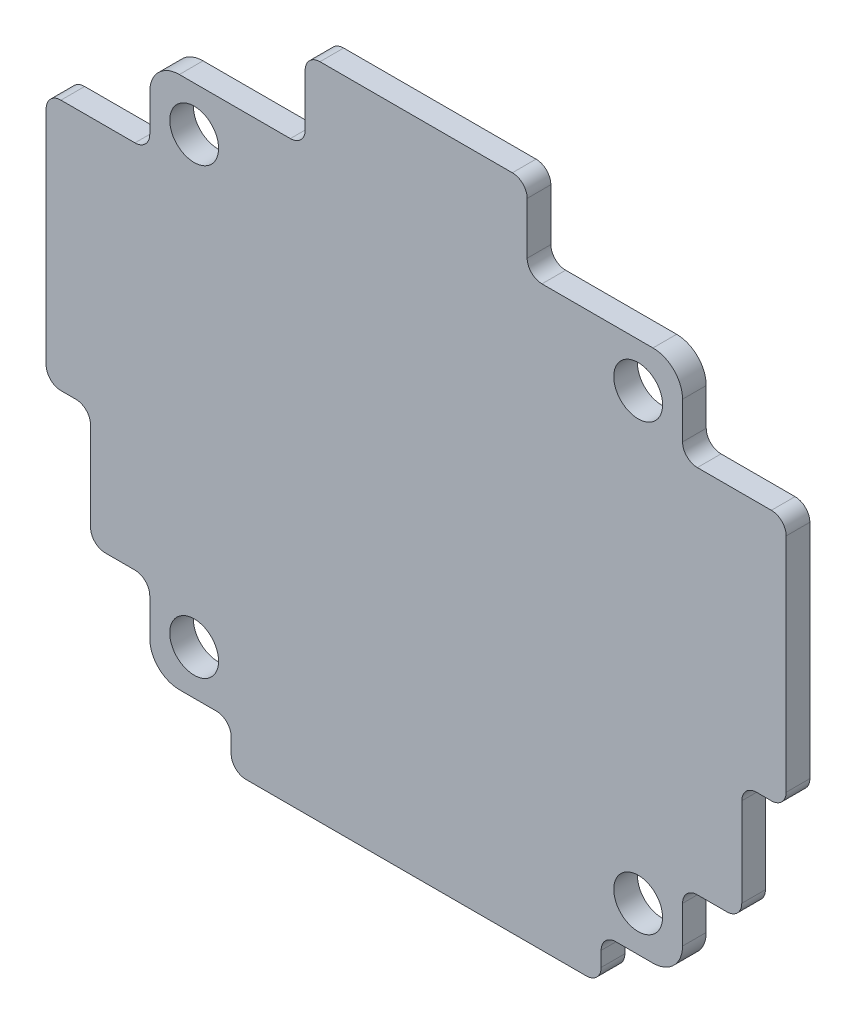
SolidWorks part; units mm, degrees
ref_plane "정면" through (0, 0, 0) normal (0, 0, 1) x (1, 0, 0)
ref_plane "윗면" through (0, 0, 0) normal (0, 1, 0) x (1, 0, 0)
ref_plane "우측면" through (0, 0, 0) normal (1, 0, 0) x (0, 0, -1)
sketch "스케치1" plane through (0, 0, 0) normal (0, 0, 1) x (1, 0, 0)
  line L1 (18, 18) -> (-18, 18)
  line L2 (18, 18) -> (18, -18)
  line L3 (18, -18) -> (-18, -18)
  line L4 (-18, 18) -> (-18, -18)
  line L5 (18, 18) -> (-18, -18) construction
  line L6 (18, -18) -> (-18, 18) construction
  point P0 (0, 0)
  dimension "D1" = 36
  dimension "D2" = 36
extrude "Body" add sketch "스케치1" along normal blind 1.6
sketch "스케치2" plane through (0, 0, 1.6) normal (0, 0, 1) x (1, 0, 0)
  line L1 (15, -15) -> (-15, -15) construction
  line L2 (15, -15) -> (15, 15) construction
  line L3 (15, 15) -> (-15, 15) construction
  line L4 (-15, -15) -> (-15, 15) construction
  line L5 (15, -15) -> (-15, 15) construction
  line L6 (15, 15) -> (-15, -15) construction
  circle A0 centre (-15, 15) radius 1.65
  circle A1 centre (15, 15) radius 1.65
  circle A2 centre (15, -15) radius 1.65
  circle A3 centre (-15, -15) radius 1.65
  point P0 (0, 0)
  dimension "D3" = 3.3
  dimension "D1" = 30
  dimension "D2" = 30
  dimension "D4" = 2
  dimension "D5" = 2
extrude "BoltHole_M3_pillar" cut sketch "스케치2" against normal through all
fillet "필렛1" radius 2 4 edges at (18, -18, 0.8) (-18, -18, 0.8) (18, 18, 0.8) (-18, 18, 0.8)
sketch "스케치3" plane through (0, 0, 1.6) normal (0, 0, 1) x (1, 0, 0)
  line L0 (16, 18) -> (-16, 18) construction
  line L1 (-12.5, 18) -> (12.5, 18)
  line L2 (-12.5, 18) -> (-12.5, 33)
  line L3 (-12.5, 33) -> (12.5, 33)
  line L4 (12.5, 18) -> (12.5, 33)
  line L5 (0, 0) -> (0, 31.1932) construction
  point P9 (0, 33)
  dimension "D1" = 25
  dimension "D2" = 15
extrude "보스-돌출1" [suppressed] add sketch "스케치3" against normal up to surface (1.6 mm away)
fillet "필렛2" [suppressed] radius 2
sketch "스케치4" plane through (0, 0, 0) normal (0, 0, 1) x (1, 0, 0)
  line L0 (-18, 16) -> (-18, -16) construction
  line L1 (-18, 12.5) -> (-25, 12.5)
  line L2 (-18, 12.5) -> (-18, -4.5)
  line L3 (-22, -4.5) -> (-25, -4.5)
  line L4 (-25, 12.5) -> (-25, -4.5)
  line L10 (0, 0) -> (0, 18) construction
  line L11 (16, 18) -> (-16, 18) construction
  line L12 (25, 12.5) -> (25, -4.5)
  line L13 (22, -4.5) -> (25, -4.5)
  line L14 (18, 12.5) -> (18, -4.5)
  line L15 (18, 12.5) -> (25, 12.5)
  line L16 (-16, -18) -> (16, -18) construction
  line L17 (-7.5, 18) -> (7.5, 18)
  line L18 (-7.5, 18) -> (-7.5, 23.5)
  line L19 (-7.5, 23.5) -> (7.5, 23.5)
  line L20 (7.5, 18) -> (7.5, 23.5)
  line L21 (-12.5, -18) -> (12.5, -18)
  line L22 (-12.5, -18) -> (-12.5, -21)
  line L23 (-12.5, -21) -> (12.5, -21)
  line L24 (12.5, -18) -> (12.5, -21)
  line L26 (18, -4.5) -> (18, -12.5)
  line L27 (18, -12.5) -> (22, -12.5)
  line L28 (22, -4.5) -> (22, -12.5)
  line L30 (-22, -4.5) -> (-22, -12.5)
  line L31 (-22, -12.5) -> (-18, -12.5)
  line L32 (-18, -4.5) -> (-18, -12.5)
  point P15 (-25, 4)
  point P20 (0, 18)
  point P27 (0, -18)
  dimension "D1" = 7
  dimension "D2" = 17
  dimension "D3" = 4
  dimension "D4" = 15
  dimension "D5" = 5.5
  dimension "D6" = 3
  dimension "D7" = 25
  dimension "D8" = 4
  dimension "D9" = 8
  dimension "D10" = 4
extrude "Connectors_power" add sketch "스케치4" along normal up to surface (1.6 mm away) up to face at (-13.35, -15, 1.6)
fillet "필렛3" radius 1 20 edges at (25, 12.5, 0.8) (18, 12.5, 0.8) (25, -4.5, 0.8) (-25, -4.5, 0.8) (-25, 12.5, 0.8) (-18, 12.5, 0.8) (7.5, 18, 0.8) (7.5, 23.5, 0.8) (-7.5, 23.5, 0.8) (-7.5, 18, 0.8) (12.5, -21, 0.8) (12.5, -18, 0.8) (-12.5, -21, 0.8) (-12.5, -18, 0.8) (18, -12.5, 0.8) (22, -12.5, 0.8) (22, -4.5, 0.8) (-18, -12.5, 0.8) (-22, -12.5, 0.8) (-22, -4.5, 0.8)
